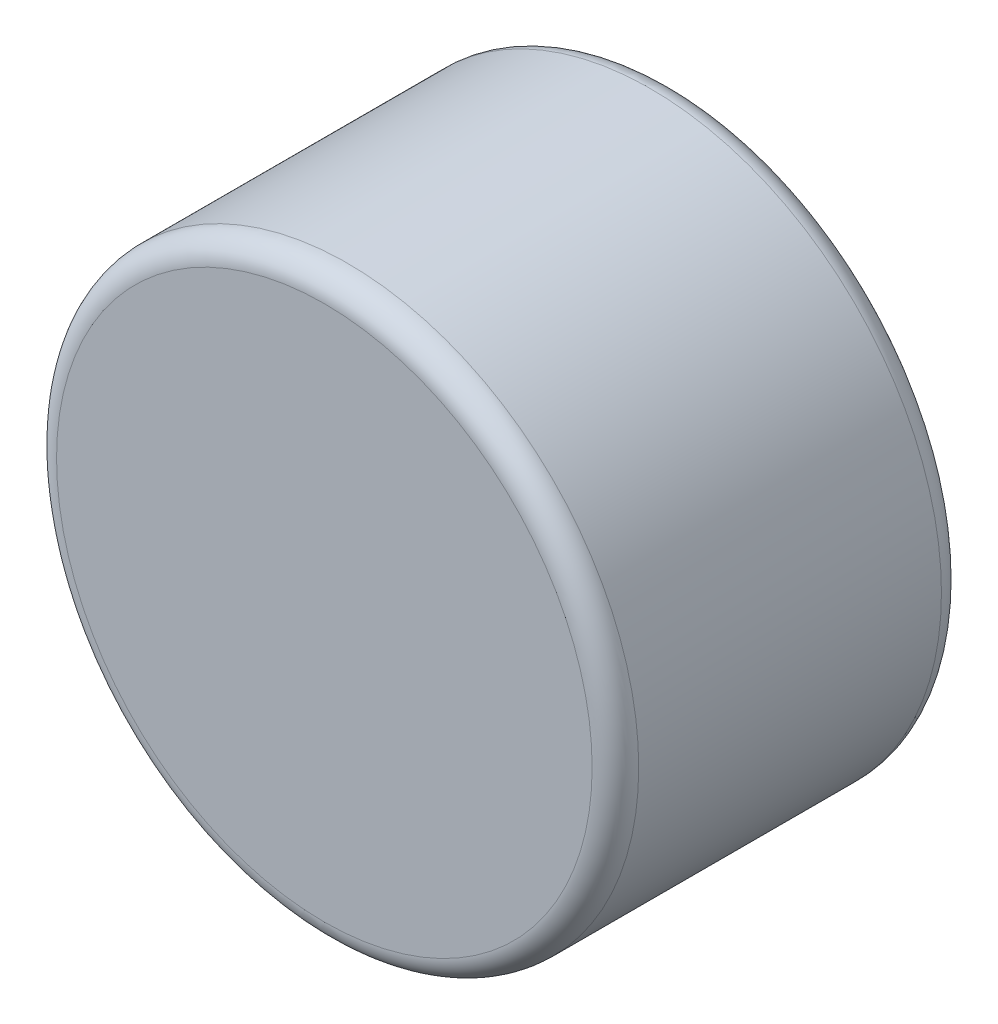
SolidWorks part; units mm, degrees
ref_plane "前视基准面" through (0, 0, 0) normal (0, 0, 1) x (1, 0, 0)
ref_plane "上视基准面" through (0, 0, 0) normal (0, 1, 0) x (1, 0, 0)
ref_plane "右视基准面" through (0, 0, 0) normal (1, 0, 0) x (0, 0, -1)
sketch "草图1" plane through (0, 0, 0) normal (0, 0, 1) x (1, 0, 0)
  circle A1 centre (0, 0) radius 2.5
  dimension "D1" = 5
extrude "凸台-拉伸1" add sketch "草图1" along normal blind 3
fillet "圆角1" radius 0.2 2 edges at (2.5, 0, 3) (2.5, 0, 0)
